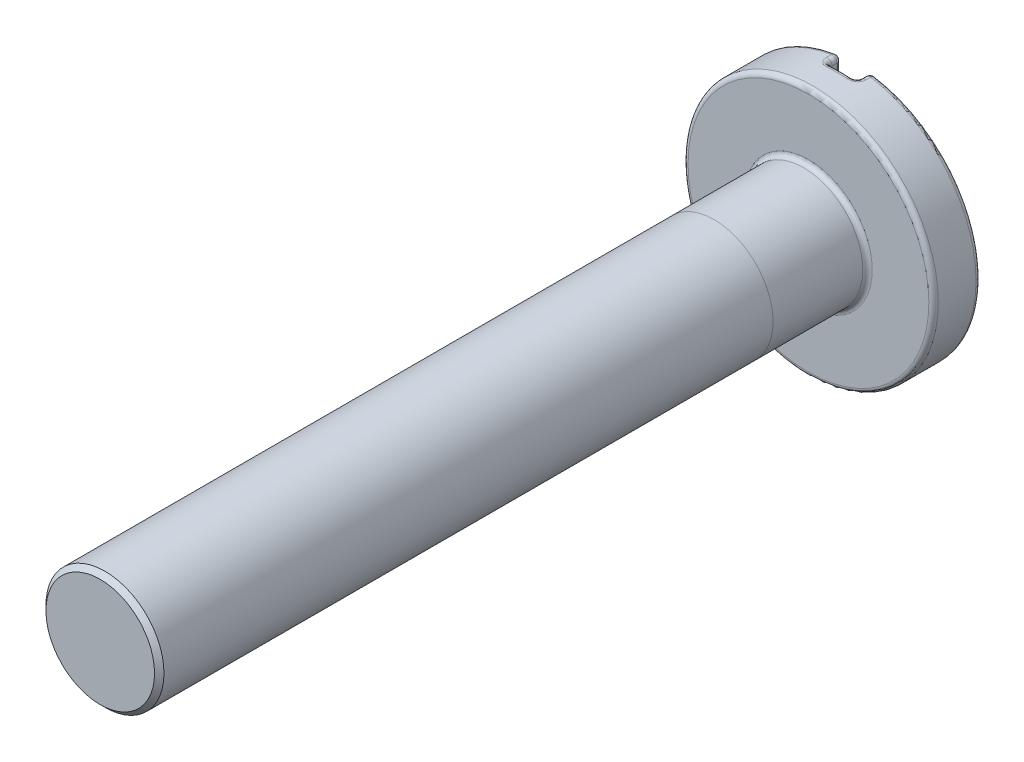
SolidWorks part; units mm, degrees
ref_plane "Front Plane" through (0, 0, 0) normal (0, 0, 1) x (1, 0, 0)
ref_plane "Top Plane" through (0, 0, 0) normal (0, 1, 0) x (1, 0, 0)
ref_plane "Right Plane" through (0, 0, 0) normal (1, 0, 0) x (0, 0, -1)
sketch "Sketch1" plane through (0, 0, 0) normal (0, 0, 1) x (1, 0, 0)
  circle A0 centre (0, 0) radius 0.625
  dimension "D1" = 1.25
extrude "Boss-Extrude1" add sketch "Sketch1" along normal blind 7.5
sketch "Sketch2" plane through (0, 0, 0) normal (0, 0, 1) x (1, 0, 0)
  circle A2 centre (0, 0) radius 1.325
  circle A3 centre (0, 0) radius 1.325
  dimension "D1" = 0.7
extrude "Boss-Extrude2" add sketch "Sketch2" against normal blind 0.5
sketch "Sketch3" plane through (0, 0, -0.5) normal (0, 0, -1) x (-1, 0, 0)
  line L1 (-0.15, 4.1969) -> (0.15, 4.1969)
  line L2 (-0.15, 4.1969) -> (-0.15, -4.1969)
  line L3 (-0.15, -4.1969) -> (0.15, -4.1969)
  line L4 (0.15, 4.1969) -> (0.15, -4.1969)
  line L5 (-0.15, 4.1969) -> (0.15, -4.1969) construction
  line L6 (-0.15, -4.1969) -> (0.15, 4.1969) construction
  point P0 (0, 0)
  dimension "D1" = 0.3
extrude "Cut-Extrude1" cut sketch "Sketch3" against normal blind 0.15
fillet "Fillet1" radius 0.05 13 edges at (0.15, 1.3165, -0.425) (0.15, -1.3165, -0.425) (-0.15, -1.3165, -0.425) (-0.15, 1.3165, -0.425) (0, -1.325, -0.35) (0, 1.325, -0.35) (0.15, 0, -0.35) (-0.15, 0, -0.35) (0.15, 0, -0.5) (1.325, 0, -0.5) (-0.15, 0, -0.5) (-1.325, 0, -0.5) (0.625, 0, 0)
fillet "Fillet2" radius 0.05 1 edges at (1.325, 0, 0)
chamfer "Chamfer1" distance 0.05 angle 45 1 edges at (0.625, 0, 7.5)
sketch "Sketch4" plane through (0, 0, 0) normal (1, 0, 0) x (0, 0, -1)
  line L0 (-1, 3.701) -> (-1, -3.2348)
  line L1 (-7.5, 0.575) -> (-7.5, -0.575) construction
  dimension "D1" = 6.5
split line "Split Line1"
